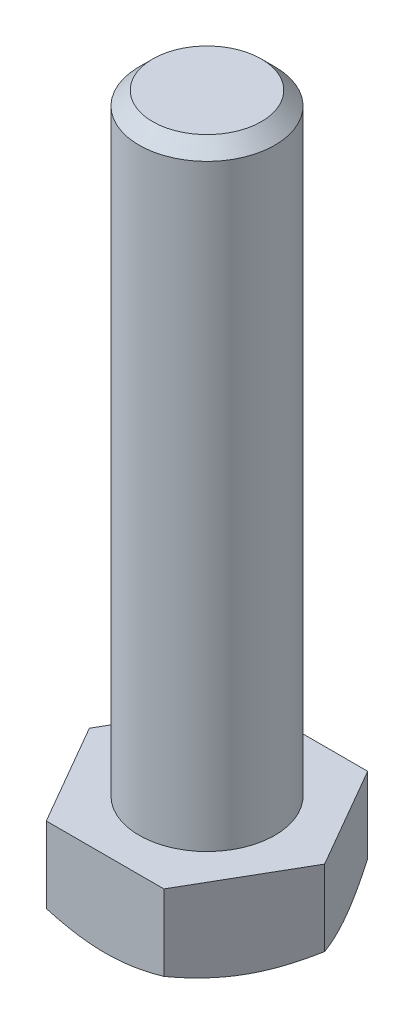
SolidWorks part; units mm, degrees
material "普通碳钢"
ref_plane "前视基准面" through (0, 0, 0) normal (0, 0, 1) x (1, 0, 0)
ref_plane "上视基准面" through (0, 0, 0) normal (0, 1, 0) x (1, 0, 0)
ref_plane "右视基准面" through (0, 0, 0) normal (1, 0, 0) x (0, 0, -1)
sketch "草图1" plane through (0, 0, 0) normal (0, 1, 0) x (1, 0, 0)
  line L1 (8.6603, -15) -> (17.3205, 0)
  line L2 (17.3205, 0) -> (8.6603, 15)
  line L3 (8.6603, 15) -> (-8.6603, 15)
  line L4 (-8.6603, 15) -> (-17.3205, 0)
  line L5 (-17.3205, 0) -> (-8.6603, -15)
  line L6 (-8.6603, -15) -> (8.6603, -15)
  circle A0 centre (0, 0) radius 15 construction
  dimension "D1" = 30
extrude "凸台-拉伸1" add sketch "草图1" along normal blind 12.5
sketch "草图2" plane through (0, 12.5, 0) normal (0, 1, 0) x (1, 0, 0)
  circle A0 centre (0, 0) radius 10
  dimension "D1" = 20
extrude "凸台-拉伸2" add sketch "草图2" along normal blind 90
cosmetic thread "装饰螺纹线1" parameters "D1"=46, "D2"=17.294
chamfer "倒角1" distance 2 angle 45 1 edges at (0, 102.5, 10)
sketch "草图3" plane through (8.6603, 0, 0) normal (0, 0, 1) x (1, 0, 0)
  line L0 (-8.6603, 0) -> (-8.6603, 12.5) construction
  line L4 (-17.3205, 12.5) -> (0, 12.5) construction
  line L6 (-23.6603, 0) -> (-25.9808, 1.3397)
  line L7 (-25.9808, 0) -> (-17.3205, 0) construction
  line L8 (-25.9808, 12.5) -> (-25.9808, 0) construction
  line L9 (-23.6603, 0) -> (-25.9808, 0)
  line L10 (-25.9808, 0) -> (-25.9808, 1.3397)
  dimension "D1" = 30
  dimension "D2" = 30
revolve "切除-旋转3" cut sketch "草图3" angle 360 about L0
